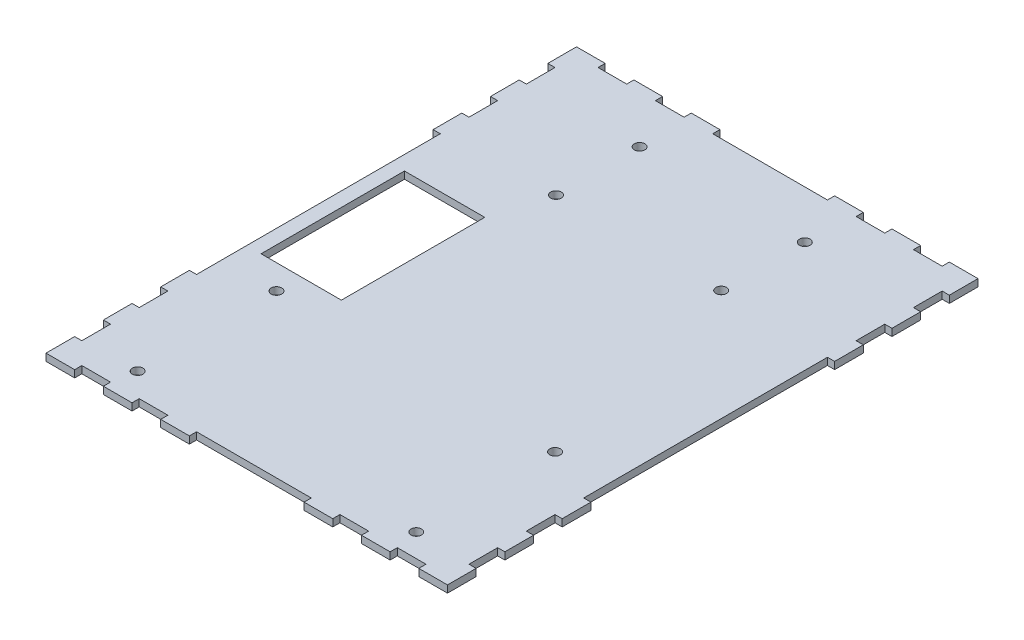
SolidWorks part; units mm, degrees
material "Acrylic (Medium-high impact)"
ref_plane "Front Plane" through (0, 0, 0) normal (0, 0, 1) x (1, 0, 0)
ref_plane "Top Plane" through (0, 0, 0) normal (0, 1, 0) x (1, 0, 0)
ref_plane "Right Plane" through (0, 0, 0) normal (1, 0, 0) x (0, 0, -1)
sketch "Sketch1" plane through (0, 0, 0) normal (0, 1, 0) x (1, 0, 0)
  line L0 (0, 209.55) -> (0, 196.85)
  line L1 (0, 0) -> (177.8, 0)
  line L2 (0, 0) -> (0, 234.95)
  line L3 (0, 234.95) -> (177.8, 234.95)
  line L4 (177.8, 0) -> (177.8, 234.95)
  line L5 (0, 234.95) -> (3.175, 234.95)
  line L6 (0, 234.95) -> (0, 0)
  line L7 (0, 0) -> (3.175, 0)
  line L8 (3.175, 234.95) -> (3.175, 0)
  line L9 (177.8, 234.95) -> (174.625, 234.95)
  line L10 (177.8, 234.95) -> (177.8, 0)
  line L11 (177.8, 0) -> (174.625, 0)
  line L12 (174.625, 234.95) -> (174.625, 0)
  line L13 (0, 234.95) -> (3.175, 234.95)
  line L14 (0, 234.95) -> (0, 222.25)
  line L15 (0, 222.25) -> (3.175, 222.25)
  line L16 (3.175, 234.95) -> (3.175, 222.25)
  line L17 (0, 209.55) -> (3.175, 209.55)
  line L18 (3.175, 209.55) -> (3.175, 196.85)
  line L19 (0, 196.85) -> (3.175, 196.85)
  line L20 (0, 184.15) -> (0, 171.45)
  line L21 (0, 184.15) -> (3.175, 184.15)
  line L22 (3.175, 184.15) -> (3.175, 171.45)
  line L23 (0, 171.45) -> (3.175, 171.45)
  line L24 (0, 117.475) -> (177.8, 117.475) construction
  line L25 (88.9, 234.95) -> (88.9, 0) construction
  line L26 (177.8, 171.45) -> (174.625, 171.45)
  line L27 (174.625, 184.15) -> (174.625, 171.45)
  line L28 (177.8, 184.15) -> (174.625, 184.15)
  line L29 (177.8, 184.15) -> (177.8, 171.45)
  line L30 (177.8, 196.85) -> (174.625, 196.85)
  line L31 (174.625, 209.55) -> (174.625, 196.85)
  line L32 (177.8, 209.55) -> (174.625, 209.55)
  line L33 (174.625, 234.95) -> (174.625, 222.25)
  line L34 (177.8, 222.25) -> (174.625, 222.25)
  line L35 (177.8, 234.95) -> (177.8, 222.25)
  line L36 (177.8, 234.95) -> (174.625, 234.95)
  line L37 (177.8, 234.95) -> (177.8, 0)
  line L38 (177.8, 234.95) -> (174.625, 234.95)
  line L39 (177.8, 209.55) -> (177.8, 196.85)
  line L40 (177.8, 25.4) -> (177.8, 38.1)
  line L41 (177.8, 0) -> (174.625, 0)
  line L42 (177.8, 0) -> (174.625, 0)
  line L43 (177.8, 0) -> (177.8, 12.7)
  line L44 (177.8, 12.7) -> (174.625, 12.7)
  line L45 (174.625, 0) -> (174.625, 12.7)
  line L46 (177.8, 25.4) -> (174.625, 25.4)
  line L47 (174.625, 25.4) -> (174.625, 38.1)
  line L48 (177.8, 38.1) -> (174.625, 38.1)
  line L49 (177.8, 50.8) -> (177.8, 63.5)
  line L50 (177.8, 50.8) -> (174.625, 50.8)
  line L51 (174.625, 50.8) -> (174.625, 63.5)
  line L52 (177.8, 63.5) -> (174.625, 63.5)
  line L53 (0, 63.5) -> (3.175, 63.5)
  line L54 (3.175, 50.8) -> (3.175, 63.5)
  line L55 (0, 50.8) -> (3.175, 50.8)
  line L56 (0, 50.8) -> (0, 63.5)
  line L57 (0, 38.1) -> (3.175, 38.1)
  line L58 (3.175, 25.4) -> (3.175, 38.1)
  line L59 (0, 25.4) -> (3.175, 25.4)
  line L60 (3.175, 0) -> (3.175, 12.7)
  line L61 (0, 12.7) -> (3.175, 12.7)
  line L62 (0, 0) -> (0, 12.7)
  line L63 (0, 0) -> (3.175, 0)
  line L64 (177.8, 0) -> (174.625, 0)
  line L65 (0, 0) -> (3.175, 0)
  line L66 (0, 0) -> (177.8, 0)
  line L67 (0, 25.4) -> (0, 38.1)
  dimension "D1" = 234.95
  dimension "D2" = 177.8
  dimension "D3" = 3.175
  dimension "D4" = 3.175
  dimension "D5" = 12.7
  dimension "D6" = 3.175
  dimension "D7" = 3
extrude "Boss-Extrude1" add sketch "Sketch1" along normal blind 3.175 contours L6 L55 L8 L53 | L6 L59 L8 L57 | L61 L2 L1 L8 | L6 L23 L8 L21 | L0 L19 L8 L17 | L6 L15 L8 L3 | L4 L44 L12 L1 | L37 L48 L12 L46 | L37 L52 L12 L50 | L34 L10 L3 L12 | L10 L32 L12 L30 | L10 L28 L12 L26 | L52 L12 L26 L27 L28 L30 L31 L32 L34 L33 L3 L8 L1 L45 L44 L46 L47 L48 L50 L51
sketch "Sketch5" plane through (0, 3.175, 0) normal (0, 1, 0) x (1, 0, 0)
  line L0 (88.9, 0) -> (88.9, 18.3402) construction
  line L1 (0, 0) -> (177.8, 0) construction
  line L3 (0, 0) -> (12.7, 0)
  line L4 (0, 0) -> (0, 3.175)
  line L5 (0, 3.175) -> (12.7, 3.175)
  line L6 (12.7, 0) -> (12.7, 3.175)
  line L10 (25.4, 3.175) -> (38.1, 3.175)
  line L11 (25.4, 0) -> (38.1, 0)
  line L12 (38.1, 0) -> (38.1, 3.175)
  line L13 (25.4, 0) -> (25.4, 3.175)
  line L14 (50.8, 3.175) -> (63.5, 3.175)
  line L15 (50.8, 0) -> (63.5, 0)
  line L16 (63.5, 0) -> (63.5, 3.175)
  line L17 (50.8, 0) -> (50.8, 3.175)
  line L18 (0, 3.175) -> (177.8, 3.175)
  line L19 (127, 0) -> (127, 3.175)
  line L20 (114.3, 0) -> (114.3, 3.175)
  line L21 (127, 0) -> (114.3, 0)
  line L22 (127, 3.175) -> (114.3, 3.175)
  line L23 (152.4, 0) -> (152.4, 3.175)
  line L24 (139.7, 0) -> (139.7, 3.175)
  line L25 (152.4, 0) -> (139.7, 0)
  line L26 (152.4, 3.175) -> (139.7, 3.175)
  line L27 (165.1, 0) -> (165.1, 3.175)
  line L28 (177.8, 3.175) -> (165.1, 3.175)
  line L29 (177.8, 0) -> (177.8, 3.175)
  line L30 (177.8, 0) -> (165.1, 0)
  line L63 (0, 63.5) -> (0, 50.8)
  line L64 (0, 50.8) -> (3.175, 50.8)
  line L65 (3.175, 50.8) -> (3.175, 38.1)
  line L66 (3.175, 38.1) -> (0, 38.1)
  line L67 (0, 38.1) -> (0, 25.4)
  line L68 (0, 25.4) -> (3.175, 25.4)
  line L69 (3.175, 25.4) -> (3.175, 12.7)
  line L70 (3.175, 12.7) -> (0, 12.7)
  line L71 (0, 12.7) -> (0, 0)
  line L72 (0, 0) -> (177.8, 0)
  line L73 (177.8, 0) -> (177.8, 12.7)
  line L74 (177.8, 12.7) -> (174.625, 12.7)
  line L75 (174.625, 12.7) -> (174.625, 25.4)
  line L76 (174.625, 25.4) -> (177.8, 25.4)
  line L77 (177.8, 25.4) -> (177.8, 38.1)
  line L78 (177.8, 38.1) -> (174.625, 38.1)
  line L79 (174.625, 38.1) -> (174.625, 50.8)
  line L80 (174.625, 50.8) -> (177.8, 50.8)
  line L81 (177.8, 50.8) -> (177.8, 63.5)
  line L82 (177.8, 63.5) -> (174.625, 63.5)
  line L83 (174.625, 63.5) -> (174.625, 171.45)
  line L84 (174.625, 171.45) -> (177.8, 171.45)
  line L85 (177.8, 171.45) -> (177.8, 184.15)
  line L86 (177.8, 184.15) -> (174.625, 184.15)
  line L87 (174.625, 184.15) -> (174.625, 196.85)
  line L88 (174.625, 196.85) -> (177.8, 196.85)
  line L89 (177.8, 196.85) -> (177.8, 209.55)
  line L90 (177.8, 209.55) -> (174.625, 209.55)
  line L91 (174.625, 209.55) -> (174.625, 222.25)
  line L92 (174.625, 222.25) -> (177.8, 222.25)
  line L93 (177.8, 222.25) -> (177.8, 234.95)
  line L94 (177.8, 234.95) -> (0, 234.95)
  line L95 (0, 234.95) -> (0, 222.25)
  line L96 (0, 222.25) -> (3.175, 222.25)
  line L97 (3.175, 222.25) -> (3.175, 209.55)
  line L98 (3.175, 209.55) -> (0, 209.55)
  line L99 (0, 209.55) -> (0, 196.85)
  line L100 (0, 196.85) -> (3.175, 196.85)
  line L101 (3.175, 196.85) -> (3.175, 184.15)
  line L102 (3.175, 184.15) -> (0, 184.15)
  line L103 (0, 184.15) -> (0, 171.45)
  line L104 (0, 171.45) -> (3.175, 171.45)
  line L105 (3.175, 171.45) -> (3.175, 63.5)
  line L106 (3.175, 63.5) -> (0, 63.5)
  line L107 (0, 63.5) -> (0, 50.8)
  line L108 (0, 50.8) -> (3.175, 50.8)
  line L109 (3.175, 50.8) -> (3.175, 38.1)
  line L110 (3.175, 38.1) -> (0, 38.1)
  line L111 (0, 38.1) -> (0, 25.4)
  line L112 (0, 25.4) -> (3.175, 25.4)
  line L113 (3.175, 25.4) -> (3.175, 12.7)
  line L114 (3.175, 12.7) -> (0, 12.7)
  line L115 (0, 12.7) -> (0, 0)
  line L116 (0, 0) -> (177.8, 0)
  line L117 (177.8, 0) -> (177.8, 12.7)
  line L118 (177.8, 12.7) -> (174.625, 12.7)
  line L119 (174.625, 12.7) -> (174.625, 25.4)
  line L120 (174.625, 25.4) -> (177.8, 25.4)
  line L121 (177.8, 25.4) -> (177.8, 38.1)
  line L122 (177.8, 38.1) -> (174.625, 38.1)
  line L123 (174.625, 38.1) -> (174.625, 50.8)
  line L124 (174.625, 50.8) -> (177.8, 50.8)
  line L125 (177.8, 50.8) -> (177.8, 63.5)
  line L126 (177.8, 63.5) -> (174.625, 63.5)
  line L127 (174.625, 63.5) -> (174.625, 171.45)
  line L128 (174.625, 171.45) -> (177.8, 171.45)
  line L129 (177.8, 171.45) -> (177.8, 184.15)
  line L130 (177.8, 184.15) -> (174.625, 184.15)
  line L131 (174.625, 184.15) -> (174.625, 196.85)
  line L132 (174.625, 196.85) -> (177.8, 196.85)
  line L133 (177.8, 196.85) -> (177.8, 209.55)
  line L134 (177.8, 209.55) -> (174.625, 209.55)
  line L135 (174.625, 209.55) -> (174.625, 222.25)
  line L136 (174.625, 222.25) -> (177.8, 222.25)
  line L137 (177.8, 222.25) -> (177.8, 234.95)
  line L138 (177.8, 234.95) -> (0, 234.95)
  line L139 (0, 234.95) -> (0, 222.25)
  line L140 (0, 222.25) -> (3.175, 222.25)
  line L141 (3.175, 222.25) -> (3.175, 209.55)
  line L142 (3.175, 209.55) -> (0, 209.55)
  line L143 (0, 209.55) -> (0, 196.85)
  line L144 (0, 196.85) -> (3.175, 196.85)
  line L145 (3.175, 196.85) -> (3.175, 184.15)
  line L146 (3.175, 184.15) -> (0, 184.15)
  line L147 (0, 184.15) -> (0, 171.45)
  line L148 (0, 171.45) -> (3.175, 171.45)
  line L149 (3.175, 171.45) -> (3.175, 63.5)
  line L150 (3.175, 63.5) -> (0, 63.5)
  point P22 (88.9, 3.175)
  dimension "D1" = 3.175
  dimension "D2" = 12.7
  dimension "D4" = 0
  dimension "D3" = 3
extrude "Cut-Extrude4" cut sketch "Sketch5" against normal blind 7.62 contours L6 L116 L13 L18 | L12 L116 L17 L18 | L116 L0 L18 L16 | L0 L116 L20 L18 | L19 L116 L24 L18 | L23 L116 L27 L18
ref_plane "Plane2" through (0, 0, -117.475) normal (0, 0, 1) x (1, 0, 0)
mirror "Mirror1" about plane through (0, 0, -117.475) normal (0, 0, 1) of "Cut-Extrude4"
sketch "Sketch7" plane through (0, 3.175, 0) normal (0, 1, 0) x (1, 0, 0)
  line L0 (3.175, 117.475) -> (174.625, 117.475) construction
  line L1 (3.175, 171.45) -> (3.175, 63.5) construction
  line L2 (174.625, 171.45) -> (174.625, 63.5) construction
  line L3 (3.175, 117.475) -> (9.525, 117.475) construction
  line L4 (9.525, 117.475) -> (9.525, 149.225)
  line L6 (9.525, 149.225) -> (45.085, 149.225)
  line L7 (9.525, 149.225) -> (9.525, 85.725)
  line L8 (9.525, 85.725) -> (45.085, 85.725)
  line L9 (45.085, 149.225) -> (45.085, 85.725)
  dimension "D1" = 6.35
  dimension "D2" = 31.75
  dimension "D3" = 63.5
  dimension "D4" = 35.56
extrude "Cut-Extrude5" cut sketch "Sketch7" against normal blind 7.62 contours L6 L9 L8 L7
sketch "Sketch8" plane through (0, 3.175, 0) normal (0, 1, 0) x (1, 0, 0)
  line L1 (0, 0) -> (27.2089, 0)
  line L2 (0, 0) -> (0, 13.3771)
  line L3 (0, 13.3771) -> (27.2089, 13.3771)
  line L4 (27.2089, 0) -> (27.2089, 13.3771)
  line L5 (27.2089, 13.3771) -> (150.5911, 13.3771)
  line L6 (27.2089, 13.3771) -> (27.2089, 74.8494)
  line L7 (27.2089, 74.8494) -> (150.5911, 74.8494)
  line L8 (150.5911, 13.3771) -> (150.5911, 74.8494)
  circle A0 centre (27.2089, 74.8494) radius 2.3495
  circle A1 centre (27.2089, 13.3771) radius 2.3495
  circle A2 centre (150.5911, 74.8494) radius 2.3495
  circle A3 centre (150.5911, 13.3771) radius 2.3495
  dimension "D5" = 4.699
  dimension "D6" = 4.699
  dimension "D7" = 4.699
  dimension "D8" = 4.699
  dimension "D1" = 27.2089
  dimension "D2" = 13.3771
  dimension "D3" = 123.3821
  dimension "D4" = 61.4723
extrude "Cut-Extrude6" cut sketch "Sketch8" against normal blind 7.62 contours L3 A1 L4 | L6 A1 L3 | L5 A1 L6 | L4 A1 L5 | L6 A0 L7 | L7 A0 L6 | L7 A2 L8 | L8 A2 L7 | L8 A3 L5 | L5 A3 L8
sketch "Sketch9" plane through (0, 3.175, 0) normal (0, 1, 0) x (1, 0, 0)
  line L0 (-5.2862, 234.95) -> (-5.2862, 210.5603) construction
  line L2 (-5.2862, 210.5603) -> (188.1579, 210.5603) construction
  line L3 (0, 177.8) -> (52.3212, 177.8) construction
  line L4 (0, 171.45) -> (0, 184.15) construction
  line L5 (52.3212, 177.8) -> (52.3212, 234.95) construction
  line L6 (50.8, 234.95) -> (63.5, 234.95) construction
  line L7 (88.9, 231.775) -> (88.9, 217.0356) construction
  line L8 (63.5, 231.775) -> (114.3, 231.775) construction
  line L9 (0, 234.95) -> (12.7, 234.95) construction
  line L10 (-5.2862, 210.5603) -> (-5.2862, 173.5457) construction
  line L11 (-5.2862, 173.5457) -> (186.199, 173.5457) construction
  line L12 (52.3212, 177.8) -> (52.3212, 173.5457) construction
  line L13 (52.3212, 173.5457) -> (52.3212, 210.5603) construction
  circle A0 centre (52.3212, 210.5603) radius 2.3495
  circle A1 centre (52.3212, 173.5457) radius 2.3495
  circle A2 centre (125.4788, 173.5457) radius 2.3495
  circle A3 centre (125.4788, 210.5603) radius 2.3495
  dimension "D4" = 4.699
  dimension "D5" = 4.699
  dimension "D1" = 24.3897
  dimension "D2" = 52.3212
  dimension "D3" = 37.0146
extrude "Cut-Extrude7" cut sketch "Sketch9" against normal blind 25.4
